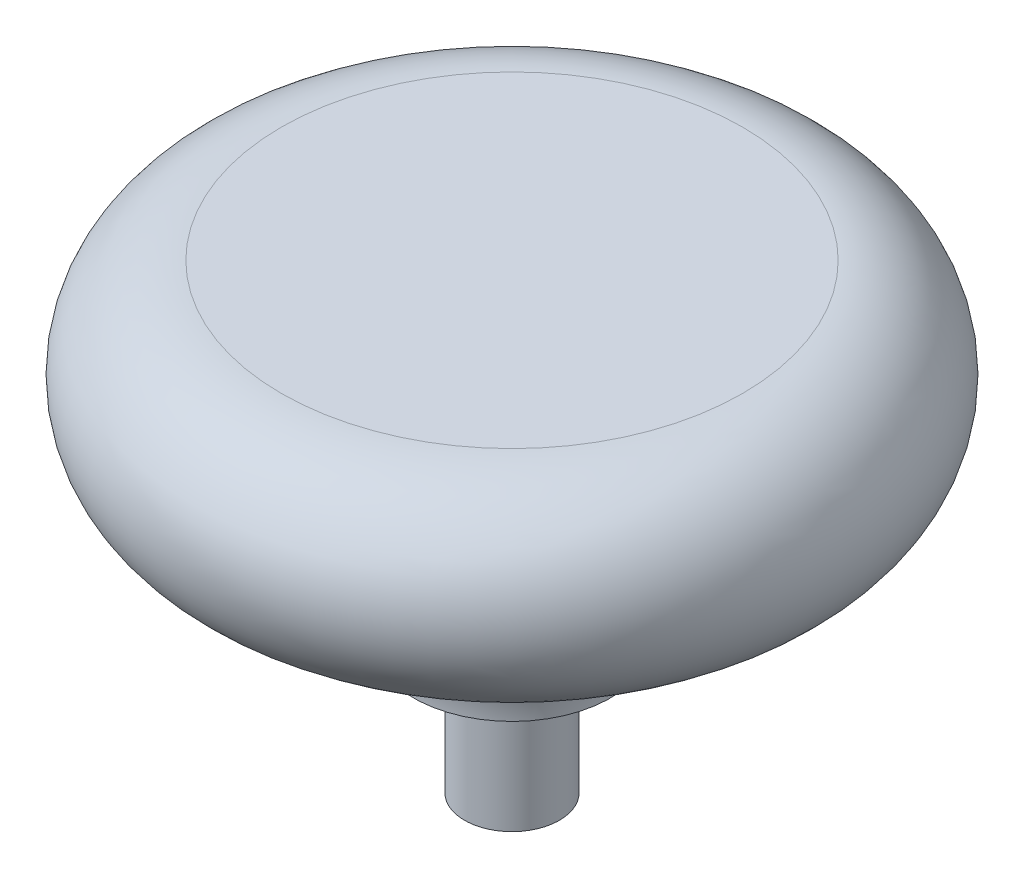
SolidWorks part; units mm, degrees
ref_plane "Front" through (0, 0, 0) normal (0, 0, 1) x (1, 0, 0)
ref_plane "Top" through (0, 0, 0) normal (0, 1, 0) x (-1, 0, 0)
ref_plane "Right" through (0, 0, 0) normal (1, 0, 0) x (0, 0, -1)
other "Configuration Table"
sketch "Sketch1" plane through (0, 0, 0) normal (0, 0, 1) x (1, 0, 0)
  line L0 (0, 0) -> (0, 36.2882) construction
  line L1 (0, 0) -> (0, 22.225)
  line L2 (0, 22.225) -> (11.1125, 22.225)
  line L4 (4.7625, 6.35) -> (2.286, 6.35)
  line L5 (2.286, 6.35) -> (2.286, 0)
  line L6 (2.286, 0) -> (0, 0)
  arc A0 (11.1125, 22.225) -> (11.1125, 12.7) centre (11.1125, 17.4625) cw
  arc A1 (11.1125, 12.7) -> (4.7625, 6.35) centre (11.1125, 6.35) ccw
  dimension "D5" = 6.35
  dimension "D6" = 4.7625
  dimension "D1" = 4.572
  dimension "D2" = 4.7625
  dimension "D3" = 6.35
  dimension "D4" = 15.875
revolve "Base-Revolve" add sketch "Sketch1" angle 360 about L0
